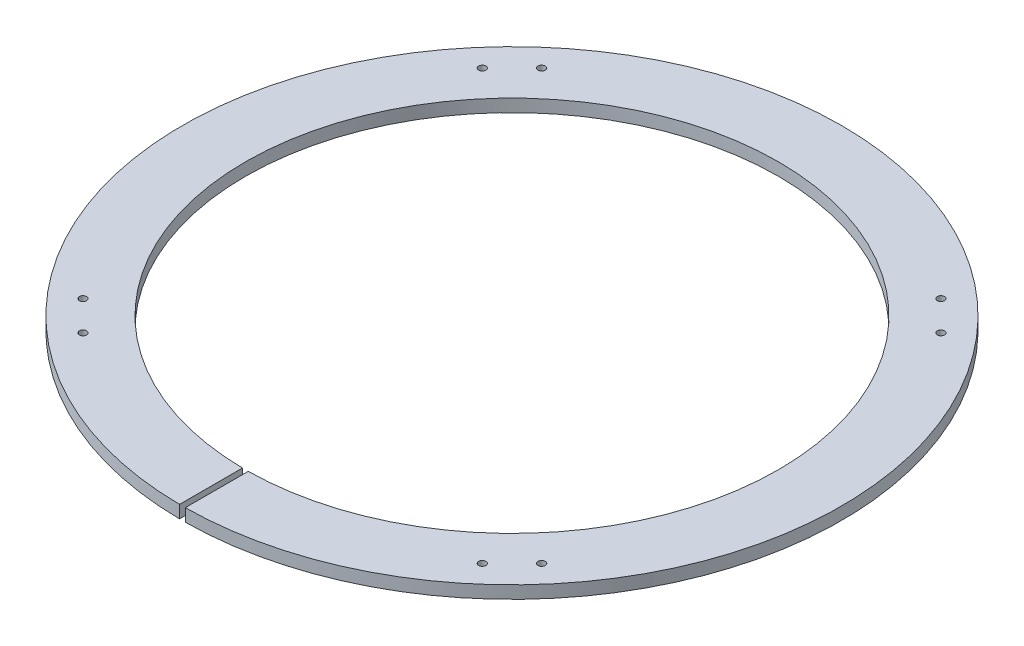
SolidWorks part; units mm, degrees
ref_plane "Front Plane" through (0, 0, 0) normal (0, 0, 1) x (1, 0, 0)
ref_plane "Top Plane" through (0, 0, 0) normal (0, 1, 0) x (1, 0, 0)
ref_plane "Right Plane" through (0, 0, 0) normal (1, 0, 0) x (0, 0, -1)
sketch "Sketch1" plane through (0, 0, 0) normal (0, 1, 0) x (1, 0, 0)
  circle A0 centre (0, 0) radius 254
  circle A1 centre (0, 0) radius 314
  dimension "D1" = 508
  dimension "D2" = 60
extrude "Boss-Extrude1" add sketch "Sketch1" along normal blind 12
sketch "Sketch2" plane through (0, 12, 0) normal (0, 1, 0) x (1, 0, 0)
  line L0 (0, -6.6) -> (0, 6.6) construction
  line L1 (-2.7449, -234.6388) -> (2.7449, -234.6388)
  line L2 (-2.7449, -234.6388) -> (-2.7449, -345.1347)
  line L3 (-2.7449, -345.1347) -> (2.7449, -345.1347)
  line L4 (2.7449, -234.6388) -> (2.7449, -345.1347)
  line L5 (-2.7449, -234.6388) -> (2.7449, -345.1347) construction
  line L6 (-2.7449, -345.1347) -> (2.7449, -234.6388) construction
  point P0 (0, -289.8868)
extrude "Cut-Extrude1" cut sketch "Sketch2" against normal through all
sketch "Sketch3" plane through (0, 12, 0) normal (0, 1, 0) x (1, 0, 0)
  line L0 (0, 0) -> (204.3539, -204.3539) construction
  line L1 (190.2117, -218.496) -> (218.496, -190.2117) construction
  line L2 (0, -6.6) -> (0, 6.6) construction
  circle A0 centre (190.2117, -218.496) radius 3.45
  circle A1 centre (218.496, -190.2117) radius 3.45
  point P6 (204.3539, -204.3539)
  dimension "D4" = 6.9
  dimension "D5" = 6.9
  dimension "D1" = 40
  dimension "D2" = 289
  dimension "D3" = 45
extrude "screw hole" cut sketch "Sketch3" against normal through all
sketch "Sketch4" plane through (0, 0, 0) normal (1, 0, 0) x (0, 0, -1)
  line L0 (0, 0) -> (0, 128.6189) construction
pattern_circular "CirPattern1" count 4 over 360 about axis through (0, 0, 0) along (0, 1, 0) of "screw hole"
equation "\"D5@Sketch3\"=\"D4@Sketch3\""
